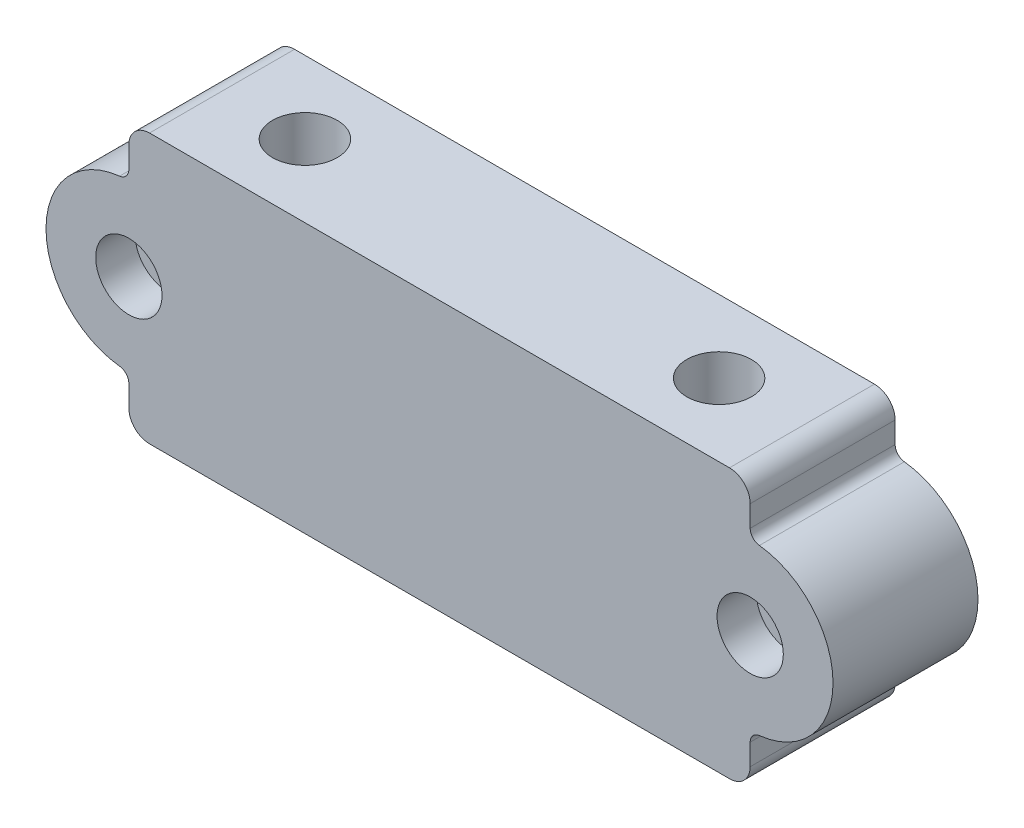
SolidWorks part; units mm, degrees
material "6061-T6 (SS)"
ref_plane "X-Y Datum" through (0, 0, 0) normal (0, 0, 1) x (1, 0, 0)
ref_plane "X-Z Datum" through (0, 0, 0) normal (0, 1, 0) x (1, 0, 0)
ref_plane "Y-Z Datum" through (0, 0, 0) normal (1, 0, 0) x (0, 0, -1)
other "Center of Mass"
other "Graphic1"
other "Graphic (Closed) -1"
other "Graphic2"
other "Graphic (Closed) -2"
other "Graphic3"
other "Graphic (Closed) -3"
sketch "Sketch1" plane through (0, 0, 0) normal (0, 1, 0) x (1, 0, 0)
  line L0 (101.6, 8.89) -> (76.2, 8.89) construction
  line L1 (101.6, 17.78) -> (0, 17.78)
  line L2 (101.6, 17.78) -> (101.6, 0)
  line L3 (101.6, 0) -> (0, 0)
  line L5 (0, 31.6293) -> (0, -17.6841) construction
  line L6 (0, 17.78) -> (0, 0)
  line L7 (76.2, 8.89) -> (25.4, 8.89) construction
  line L8 (25.4, 8.89) -> (0, 8.89) construction
  circle A0 centre (76.2, 8.89) radius 3.9688
  circle A1 centre (25.4, 8.89) radius 3.9687
  point P12 (50.8, 8.89)
  point P13 (50.8, 17.78)
  dimension "D3" = 7.9375
  dimension "D1" = 101.6
  dimension "D2" = 17.78
  dimension "D4" = 50.8
extrude "Boss-Extrude1" add sketch "Sketch1" against normal blind 33.02
sketch "Sketch2" plane through (0, 0, 0) normal (0, 0, 1) x (1, 0, 0)
  line L4 (0, -33.02) -> (0, 0) construction
  line L5 (0, -33.02) -> (101.6, -33.02) construction
  line L8 (101.6, -33.02) -> (101.6, 0) construction
  circle A0 centre (88.9, -16.51) radius 2.4892
  circle A1 centre (12.7, -16.51) radius 2.4892
  dimension "D3" = 4.9784
  dimension "D1" = 12.7
  dimension "D5" = 16.51
  dimension "D6" = 12.7
  dimension "D2" = 16.51
extrude "Cut-Extrude1" cut sketch "Sketch2" against normal up to surface (17.78 mm away) up to face at (50.8, -16.51, -17.78)
sketch "Sketch3" plane through (0, 0, 0) normal (0, 0, 1) x (1, 0, 0)
  circle A0 centre (88.9, -16.51) radius 4.064
  circle A3 centre (12.7, -16.51) radius 4.064
  circle A4 centre (12.7, -16.51) radius 2.4892 construction
  dimension "D1" = 8.128
extrude "Cut-Extrude2" cut sketch "Sketch3" against normal blind 4.826
ref_plane "Plane1" through (0, -16.51, 0) normal (0, 1, 0) x (1, 0, 0)
ref_plane "Plane2" through (0, -16.51, 0) normal (0, 1, 0) x (1, 0, 0)
sketch "Sketch5" plane through (0, 0, 0) normal (0, 0, 1) x (1, 0, 0)
  line L8 (0, -33.02) -> (101.6, -33.02) construction
  line L18 (0, -33.02) -> (0, 0) construction
  line L19 (50.8, 0) -> (50.8, -33.02) construction
  line L20 (0, 0) -> (101.6, 0) construction
  line B0 (12.7, -5.1508) -> (12.7, 0)
  line B1 (0, 0) -> (12.7, 0)
  line B2 (0, -33.02) -> (0, 0)
  line B3 (12.7, -33.02) -> (0, -33.02)
  line B4 (12.7, -27.8692) -> (12.7, -33.02)
  arc B5 (12.7, -5.1508) -> (11.5711, -6.4129) centre (11.43, -5.1508) cw
  arc B6 (12.7, -27.8692) -> (11.5711, -26.6071) centre (11.43, -27.8692) ccw
  arc B7 (11.5711, -26.6071) -> (11.5711, -6.4129) centre (12.7, -16.51) cw
  line B8 (88.9, -5.1508) -> (88.9, 0)
  line B9 (101.6, 0) -> (88.9, 0)
  line B10 (101.6, -33.02) -> (101.6, 0)
  line B11 (88.9, -33.02) -> (101.6, -33.02)
  line B12 (88.9, -27.8692) -> (88.9, -33.02)
  arc B13 (88.9, -5.1508) -> (90.0289, -6.4129) centre (90.17, -5.1508) ccw
  arc B14 (88.9, -27.8692) -> (90.0289, -26.6071) centre (90.17, -27.8692) cw
  arc B15 (90.0289, -26.6071) -> (90.0289, -6.4129) centre (88.9, -16.51) ccw
sketch_block_instance "Block2-1"
sketch_block "Block2"
sketch_block_instance "Block2-2"
extrude "Cut-Extrude3" cut sketch "Sketch5" against normal through all
fillet "Fillet1" radius 2.54 4 edges at (12.7, 0, -8.89) (88.9, 0, -8.89) (88.9, -33.02, -8.89) (12.7, -33.02, -8.89)
ref_point "Point1"
ref_point "Point2"
